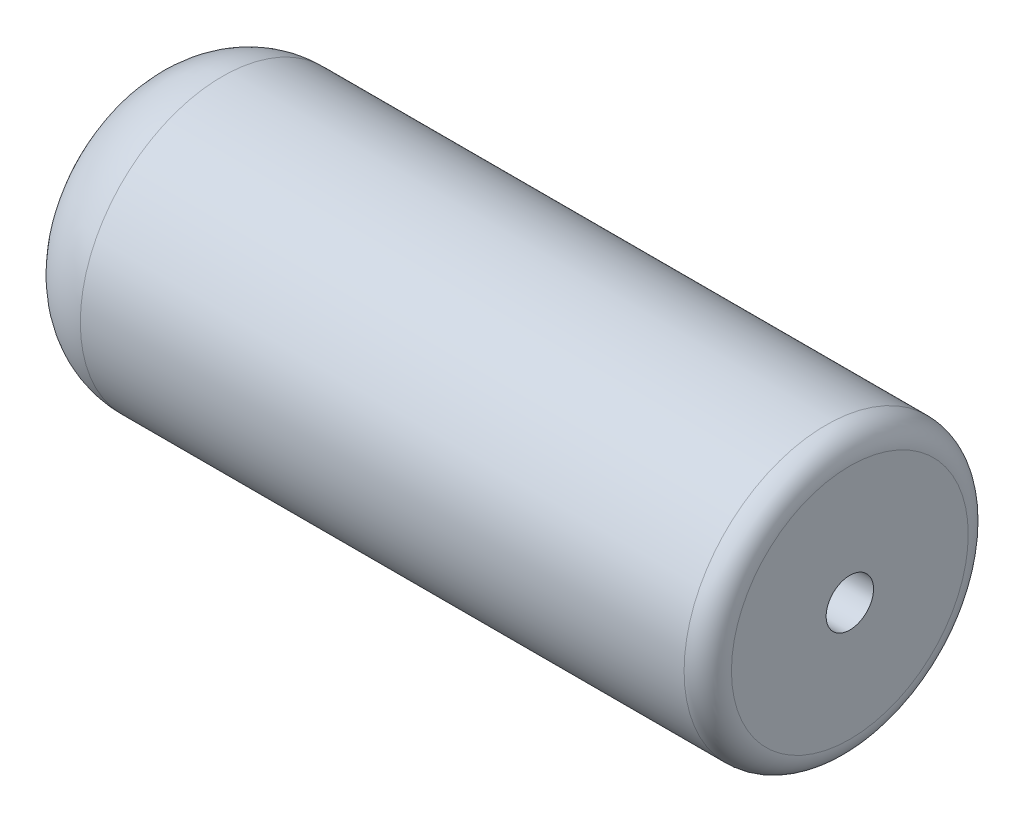
SolidWorks part; units mm, degrees
ref_plane "Front Plane" through (0, 0, 0) normal (0, 0, 1) x (1, 0, 0)
ref_plane "Top Plane" through (0, 0, 0) normal (0, 1, 0) x (1, 0, 0)
ref_plane "Right Plane" through (0, 0, 0) normal (1, 0, 0) x (0, 0, -1)
sketch "Sketch2" plane through (0, 0, 0) normal (1, 0, 0) x (0, 0, -1)
  circle A0 centre (0, 0) radius 15.24
  dimension "D1" = 30.48
extrude "Boss-Extrude2" add sketch "Sketch2" along normal blind 76.2
sketch "Sketch3" plane through (76.2, 0, 0) normal (1, 0, 0) x (0, 0, -1)
  circle A0 centre (0, 0) radius 2.54
  dimension "D1" = 5.08
extrude "Cut-Extrude1" cut sketch "Sketch3" against normal blind 63.5
fillet "Fillet1" radius 8.89 1 edges at (0, 0, -15.24)
fillet "Fillet2" radius 2.54 1 edges at (76.2, 0, -15.24)
